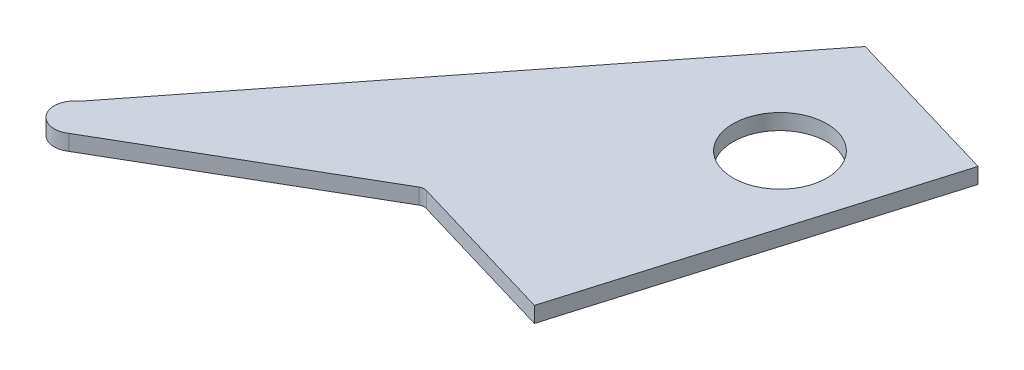
SolidWorks part; units mm, degrees
ref_plane "Front Plane" through (0, 0, 0) normal (0, 0, 1) x (1, 0, 0)
ref_plane "Top Plane" through (0, 0, 0) normal (0, 1, 0) x (1, 0, 0)
ref_plane "Right Plane" through (0, 0, 0) normal (1, 0, 0) x (0, 0, -1)
sketch "Sketch1" plane through (0, 0, 0) normal (0, 1, 0) x (1, 0, 0)
  line L0 (53.8544, 73.3734) -> (102.5625, 58.9454)
  line L1 (22.9946, -31.525) -> (-44.3261, -70.5626)
  line L2 (-51.2626, -60.5757) -> (53.8544, 73.3734)
  line L4 (102.5625, 58.9454) -> (71.7331, -45.1328)
  line L5 (71.7331, -45.1328) -> (24.9902, -31.2869)
  arc A0 (-44.3261, -70.5626) -> (-51.2626, -60.5757) centre (-47.7944, -65.5691) cw
  arc A2 (22.9946, -31.525) -> (24.9902, -31.2869) centre (24.2688, -33.7223) cw
  dimension "D1" = 2.54
extrude "Boss-Extrude1" add sketch "Sketch1" along normal blind 4.7625
sketch "Sketch2" plane through (0, 4.7625, 0) normal (0, 1, 0) x (1, 0, 0)
  circle A0 centre (68.3614, 32.9161) radius 14.2875
extrude "Cut-Extrude1" cut sketch "Sketch2" against normal through all
